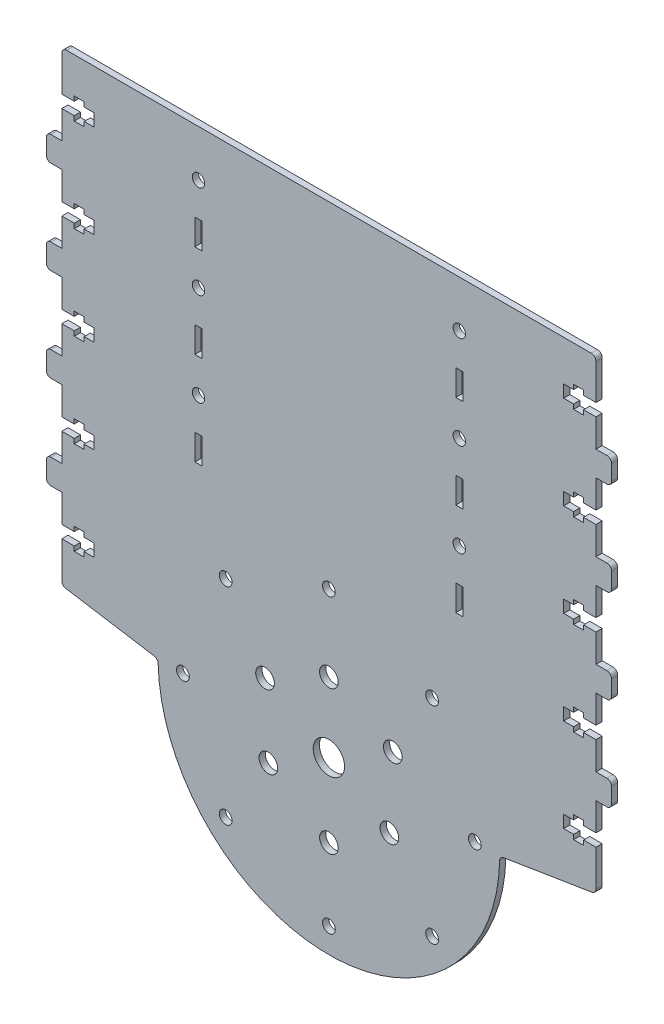
SolidWorks part; units mm, degrees
ref_plane "前视基准面" through (0, 0, 0) normal (0, 0, 1) x (1, 0, 0)
ref_plane "上视基准面" through (0, 0, 0) normal (0, 1, 0) x (1, 0, 0)
ref_plane "右视基准面" through (0, 0, 0) normal (1, 0, 0) x (0, 0, -1)
sketch "草图1" plane through (0, 0, 0) normal (0, 0, 1) x (1, 0, 0)
  line L9 (143, 46) -> (147, 46)
  line L10 (147, 46) -> (147, 44.5)
  line L11 (147, 44.5) -> (150.2, 44.5)
  line L12 (150.2, 44.5) -> (150.2, 46)
  line L13 (150.2, 46) -> (153.4, 46)
  line L14 (153.4, 46) -> (153.4, 50)
  line L23 (143, 48) -> (141.6922, 48) construction
  line L24 (143, 46) -> (143, 50) construction
  line L25 (150.2, 51.5) -> (150.2, 50)
  line L26 (147, 50) -> (147, 51.5)
  line L27 (150.2, 50) -> (153.4, 50)
  line L28 (147, 51.5) -> (150.2, 51.5)
  line L29 (143, 50) -> (147, 50)
  line L31 (143, 29) -> (138, 29)
  line L32 (138, 29) -> (138, 37)
  line L33 (138, 37) -> (143, 37)
  line L34 (143, 37) -> (143, 46)
  line L35 (138, 33) -> (143, 33) construction
  line L43 (143, 119) -> (143, 123)
  line L44 (229, -79) -> (229, -87) construction
  line L45 (143, 20) -> (143, 16) construction
  line L69 (143, -97) -> (311, -97) construction
  line L70 (143, 18) -> (141.6922, 18) construction
  line L71 (143, 16) -> (147, 16)
  line L72 (147, 16) -> (147, 14.5)
  line L73 (147, 14.5) -> (150.2, 14.5)
  line L98 (150.2, 14.5) -> (150.2, 16)
  line L123 (150.2, 16) -> (153.4, 16)
  line L124 (150.2, 21.5) -> (150.2, 20)
  line L125 (147, 20) -> (147, 21.5)
  line L126 (150.2, 20) -> (153.4, 20)
  line L127 (147, 21.5) -> (150.2, 21.5)
  line L128 (143, 20) -> (147, 20)
  line L129 (143, 7) -> (143, 16)
  line L130 (143, 16) -> (147, 16)
  line L131 (147, 14.5) -> (150.2, 14.5)
  line L132 (143, 16) -> (147, 16)
  line L133 (147, 16) -> (147, 14.5)
  line L134 (147, 14.5) -> (150.2, 14.5)
  line L135 (150.2, 14.5) -> (150.2, 16)
  line L136 (150.2, 16) -> (153.4, 16)
  line L137 (150.2, 21.5) -> (150.2, 20)
  line L138 (147, 20) -> (147, 21.5)
  line L139 (150.2, 20) -> (153.4, 20)
  line L140 (147, 21.5) -> (150.2, 21.5)
  line L141 (143, 20) -> (147, 20)
  line L142 (150.2, 16) -> (153.4, 16)
  line L143 (147, 16) -> (147, 14.5)
  line L144 (150.2, 14.5) -> (150.2, 16)
  line L145 (150.2, 20) -> (153.4, 20)
  line L146 (150.2, 21.5) -> (150.2, 20)
  line L147 (147, 21.5) -> (150.2, 21.5)
  line L148 (147, 20) -> (147, 21.5)
  line L149 (143, 20) -> (147, 20)
  line L150 (143, 46) -> (147, 46)
  line L151 (147, 46) -> (147, 44.5)
  line L152 (147, 44.5) -> (150.2, 44.5)
  line L153 (150.2, 44.5) -> (150.2, 46)
  line L154 (150.2, 46) -> (153.4, 46)
  line L155 (150.2, 51.5) -> (150.2, 50)
  line L156 (147, 50) -> (147, 51.5)
  line L157 (150.2, 50) -> (153.4, 50)
  line L158 (143, 46) -> (147, 46)
  line L159 (147, 44.5) -> (150.2, 44.5)
  line L160 (150.2, 46) -> (153.4, 46)
  line L161 (147, 46) -> (147, 44.5)
  line L162 (150.2, 44.5) -> (150.2, 46)
  line L163 (150.2, 50) -> (153.4, 50)
  line L164 (150.2, 51.5) -> (150.2, 50)
  line L165 (147, 51.5) -> (150.2, 51.5)
  line L166 (147, 50) -> (147, 51.5)
  line L167 (143, 50) -> (147, 50)
  line L168 (147, 51.5) -> (150.2, 51.5)
  line L169 (143, 50) -> (147, 50)
  line L170 (143, 29) -> (143, 20)
  line L171 (143, 16) -> (147, 16)
  line L172 (147, 14.5) -> (150.2, 14.5)
  line L173 (150.2, 16) -> (153.4, 16)
  line L174 (147, 16) -> (147, 14.5)
  line L175 (150.2, 14.5) -> (150.2, 16)
  line L177 (153.4, 20) -> (153.4, 16)
  line L178 (150.2, 20) -> (153.4, 20)
  line L179 (150.2, 21.5) -> (150.2, 20)
  line L180 (147, 21.5) -> (150.2, 21.5)
  line L181 (147, 20) -> (147, 21.5)
  line L182 (143, 20) -> (147, 20)
  line L183 (138, 3) -> (143, 3) construction
  line L184 (138, -1) -> (143, -1)
  line L185 (138, 7) -> (138, -1)
  line L186 (143, 7) -> (138, 7)
  line L187 (138, 93) -> (143, 93) construction
  line L188 (143, 78) -> (141.6922, 78) construction
  line L189 (272.15, 28.85) -> (269.85, 37.15) construction
  line L190 (138, 63) -> (143, 63) construction
  line L191 (143, 89) -> (138, 89)
  line L192 (138, 89) -> (138, 97)
  line L193 (138, 97) -> (143, 97)
  line L194 (143, 76) -> (147, 76)
  line L195 (147, 76) -> (147, 74.5)
  line L196 (147, 74.5) -> (150.2, 74.5)
  line L197 (150.2, 74.5) -> (150.2, 76)
  line L198 (150.2, 76) -> (153.4, 76)
  line L199 (143, 59) -> (143, 50)
  line L200 (138, 59) -> (143, 59)
  line L201 (153.4, 76) -> (153.4, 80)
  line L202 (150.2, 81.5) -> (150.2, 80)
  line L203 (143, 46) -> (147, 46)
  line L204 (147, 44.5) -> (150.2, 44.5)
  line L205 (150.2, 46) -> (153.4, 46)
  line L206 (147, 46) -> (147, 44.5)
  line L207 (150.2, 44.5) -> (150.2, 46)
  line L208 (150.2, 50) -> (153.4, 50)
  line L209 (150.2, 51.5) -> (150.2, 50)
  line L210 (147, 51.5) -> (150.2, 51.5)
  line L211 (147, 50) -> (147, 51.5)
  line L212 (143, 50) -> (147, 50)
  line L213 (272.15, 37.15) -> (269.85, 28.85) construction
  line L214 (147, 80) -> (147, 81.5)
  line L215 (150.2, 80) -> (153.4, 80)
  line L216 (147, 81.5) -> (150.2, 81.5)
  line L217 (143, 80) -> (147, 80)
  line L218 (143, 67) -> (143, 76)
  line L219 (143, 76) -> (147, 76)
  line L220 (147, 76) -> (147, 74.5)
  line L221 (147, 74.5) -> (150.2, 74.5)
  line L222 (150.2, 74.5) -> (150.2, 76)
  line L223 (150.2, 76) -> (153.4, 76)
  line L224 (150.2, 81.5) -> (150.2, 80)
  line L225 (147, 80) -> (147, 81.5)
  line L227 (271, 48) -> (271, 33) construction
  line L228 (272.15, 58.85) -> (269.85, 67.15) construction
  line L229 (272.15, 67.15) -> (269.85, 58.85) construction
  line L230 (150.2, 80) -> (153.4, 80)
  line L231 (143, 76) -> (147, 76)
  line L232 (147, 74.5) -> (150.2, 74.5)
  line L233 (150.2, 76) -> (153.4, 76)
  line L234 (147, 76) -> (147, 74.5)
  line L235 (150.2, 74.5) -> (150.2, 76)
  line L253 (150.2, 80) -> (153.4, 80)
  line L254 (150.2, 81.5) -> (150.2, 80)
  line L255 (143, -27) -> (143, -97) construction
  line L256 (147, 81.5) -> (150.2, 81.5)
  line L257 (147, 80) -> (147, 81.5)
  line L258 (143, 80) -> (147, 80)
  line L259 (147, 81.5) -> (150.2, 81.5)
  line L260 (143, 80) -> (147, 80)
  line L261 (143, 89) -> (143, 80)
  line L262 (143, 76) -> (147, 76)
  line L263 (147, 74.5) -> (150.2, 74.5)
  line L264 (150.2, 76) -> (153.4, 76)
  line L265 (147, 76) -> (147, 74.5)
  line L267 (150.2, 74.5) -> (150.2, 76)
  line L269 (150.2, 80) -> (153.4, 80)
  line L270 (150.2, 81.5) -> (150.2, 80)
  line L272 (147, 81.5) -> (150.2, 81.5)
  line L273 (147, 80) -> (147, 81.5)
  line L274 (143, 80) -> (147, 80)
  line L275 (138, 59) -> (143, 59)
  line L277 (138, 67) -> (138, 59)
  line L278 (143, 67) -> (138, 67)
  line L279 (143, 110) -> (143, 106) construction
  line L280 (143, 108) -> (141.6922, 108) construction
  line L281 (272.15, 88.85) -> (269.85, 97.15) construction
  line L282 (143, 106) -> (147, 106)
  line L283 (147, 106) -> (147, 104.5)
  line L284 (147, 104.5) -> (150.2, 104.5)
  line L285 (150.2, 104.5) -> (150.2, 106)
  line L286 (150.2, 106) -> (153.4, 106)
  line L287 (150.2, 111.5) -> (150.2, 110)
  line L288 (147, 110) -> (147, 111.5)
  line L289 (150.2, 110) -> (153.4, 110)
  line L290 (147, 111.5) -> (150.2, 111.5)
  line L291 (143, 110) -> (147, 110)
  line L292 (143, 97) -> (143, 106)
  line L293 (143, 106) -> (147, 106)
  line L294 (147, 104.5) -> (150.2, 104.5)
  line L296 (143, 106) -> (147, 106)
  line L300 (147, 106) -> (147, 104.5)
  line L301 (147, 104.5) -> (150.2, 104.5)
  line L302 (150.2, 104.5) -> (150.2, 106)
  line L303 (150.2, 106) -> (153.4, 106)
  line L304 (150.2, 111.5) -> (150.2, 110)
  line L305 (147, 110) -> (147, 111.5)
  line L306 (150.2, 110) -> (153.4, 110)
  line L307 (147, 111.5) -> (150.2, 111.5)
  line L308 (143, 110) -> (147, 110)
  line L309 (150.2, 106) -> (153.4, 106)
  line L310 (147, 106) -> (147, 104.5)
  line L312 (150.2, 104.5) -> (150.2, 106)
  line L314 (150.2, 110) -> (153.4, 110)
  line L315 (150.2, 111.5) -> (150.2, 110)
  line L317 (147, 111.5) -> (150.2, 111.5)
  line L320 (147, 110) -> (147, 111.5)
  line L321 (143, 110) -> (147, 110)
  line L322 (143, 119) -> (143, 110)
  line L323 (143, 106) -> (147, 106)
  line L324 (147, 104.5) -> (150.2, 104.5)
  line L325 (150.2, 106) -> (153.4, 106)
  line L326 (147, 106) -> (147, 104.5)
  line L327 (150.2, 104.5) -> (150.2, 106)
  line L328 (153.4, 110) -> (153.4, 106)
  line L329 (150.2, 110) -> (153.4, 110)
  line L330 (150.2, 111.5) -> (150.2, 110)
  line L331 (147, 111.5) -> (150.2, 111.5)
  line L332 (147, 110) -> (147, 111.5)
  line L333 (143, 110) -> (147, 110)
  line L334 (143, -14) -> (147, -14)
  line L335 (272.15, 97.15) -> (269.85, 88.85) construction
  line L336 (271, 108) -> (271, 48) construction
  line L337 (269.85, 37.15) -> (269.85, 28.85)
  line L338 (272.15, 28.85) -> (269.85, 28.85)
  line L339 (272.15, 37.15) -> (272.15, 28.85)
  line L340 (272.15, 37.15) -> (269.85, 37.15)
  line L341 (269.85, 67.15) -> (269.85, 58.85)
  line L342 (272.15, 58.85) -> (269.85, 58.85)
  line L343 (272.15, 67.15) -> (272.15, 58.85)
  line L344 (272.15, 67.15) -> (269.85, 67.15)
  line L345 (269.85, 97.15) -> (269.85, 88.85)
  line L346 (272.15, 88.85) -> (269.85, 88.85)
  line L347 (272.15, 97.15) -> (272.15, 88.85)
  line L348 (272.15, 97.15) -> (269.85, 97.15)
  line L349 (307.8, 110) -> (304.6, 110)
  line L350 (304.6, 110) -> (304.6, 106)
  line L352 (307.8, 106) -> (304.6, 106)
  line L353 (307.8, 110) -> (304.6, 110)
  line L355 (307.8, 106) -> (304.6, 106)
  line L357 (307.8, 110) -> (304.6, 110)
  line L358 (307.8, 106) -> (304.6, 106)
  line L359 (307.8, 110) -> (304.6, 110)
  line L360 (307.8, 106) -> (304.6, 106)
  line L361 (307.8, 80) -> (304.6, 80)
  line L362 (307.8, 76) -> (304.6, 76)
  line L363 (307.8, 80) -> (304.6, 80)
  line L364 (307.8, 76) -> (304.6, 76)
  line L365 (307.8, 80) -> (304.6, 80)
  line L367 (307.8, 76) -> (304.6, 76)
  line L369 (187, 108) -> (187, 48) construction
  line L370 (185.85, 97.15) -> (188.15, 97.15)
  line L371 (185.85, 97.15) -> (185.85, 88.85)
  line L372 (185.85, 88.85) -> (188.15, 88.85)
  line L373 (188.15, 97.15) -> (188.15, 88.85)
  line L374 (185.85, 97.15) -> (188.15, 88.85) construction
  line L375 (185.85, 88.85) -> (188.15, 97.15) construction
  line L387 (307.8, 80) -> (304.6, 80)
  line L389 (307.8, 50) -> (304.6, 50)
  line L391 (307.8, 46) -> (304.6, 46)
  line L392 (304.6, 76) -> (304.6, 80)
  line L420 (307.8, 76) -> (304.6, 76)
  line L421 (229, -32) -> (245.7973, -32) construction
  line L422 (229, -32) -> (253.7224, -46.2735) construction
  line L423 (185.85, 67.15) -> (188.15, 67.15)
  line L424 (185.85, 67.15) -> (185.85, 58.85)
  line L425 (185.85, 58.85) -> (188.15, 58.85)
  line L426 (188.15, 67.15) -> (188.15, 58.85)
  line L427 (185.85, 67.15) -> (188.15, 58.85) construction
  line L432 (185.85, 58.85) -> (188.15, 67.15) construction
  line L433 (307.8, 20) -> (304.6, 20)
  line L443 (187, 48) -> (187, 33) construction
  line L444 (304.6, 20) -> (304.6, 16)
  line L445 (185.85, 37.15) -> (188.15, 37.15)
  line L446 (185.85, 37.15) -> (185.85, 28.85)
  line L447 (185.85, 28.85) -> (188.15, 28.85)
  line L448 (188.15, 37.15) -> (188.15, 28.85)
  line L449 (185.85, 37.15) -> (188.15, 28.85) construction
  line L450 (185.85, 28.85) -> (188.15, 37.15) construction
  line L451 (307.8, 16) -> (304.6, 16)
  line L452 (307.8, 50) -> (304.6, 50)
  line L453 (307.8, 46) -> (304.6, 46)
  line L454 (307.8, 50) -> (304.6, 50)
  line L455 (307.8, 46) -> (304.6, 46)
  line L456 (307.8, 20) -> (304.6, 20)
  line L457 (307.8, 16) -> (304.6, 16)
  line L458 (307.8, 20) -> (304.6, 20)
  line L459 (307.8, 16) -> (304.6, 16)
  line L460 (307.8, 20) -> (304.6, 20)
  line L461 (307.8, 16) -> (304.6, 16)
  line L462 (307.8, 50) -> (304.6, 50)
  line L463 (304.6, 46) -> (304.6, 50)
  line L464 (307.8, 46) -> (304.6, 46)
  line L465 (315, 108) -> (316.3078, 108) construction
  line L466 (315, 110) -> (315, 106) construction
  line L467 (320, 63) -> (315, 63) construction
  line L468 (315, 78) -> (316.3078, 78) construction
  line L469 (320, 93) -> (315, 93) construction
  line L470 (320, 3) -> (315, 3) construction
  line L471 (315, 18) -> (316.3078, 18) construction
  line L472 (315, 20) -> (315, 16) construction
  line L473 (320, 33) -> (315, 33) construction
  line L474 (315, 46) -> (315, 50) construction
  line L475 (315, 48) -> (316.3078, 48) construction
  line L476 (315, -14) -> (315, -27)
  line L477 (315, 110) -> (311, 110)
  line L478 (311, 110) -> (311, 111.5)
  line L479 (311, 111.5) -> (307.8, 111.5)
  line L480 (307.8, 111.5) -> (307.8, 110)
  line L481 (307.8, 104.5) -> (307.8, 106)
  line L482 (311, 106) -> (311, 104.5)
  line L483 (311, 104.5) -> (307.8, 104.5)
  line L484 (315, 106) -> (311, 106)
  line L485 (315, 119) -> (315, 110)
  line L486 (315, 110) -> (311, 110)
  line L487 (311, 110) -> (311, 111.5)
  line L488 (311, 111.5) -> (307.8, 111.5)
  line L489 (307.8, 111.5) -> (307.8, 110)
  line L490 (307.8, 104.5) -> (307.8, 106)
  line L491 (311, 106) -> (311, 104.5)
  line L492 (315, 110) -> (311, 110)
  line L493 (311, 111.5) -> (307.8, 111.5)
  line L494 (311, 110) -> (311, 111.5)
  line L495 (307.8, 111.5) -> (307.8, 110)
  line L496 (307.8, 104.5) -> (307.8, 106)
  line L497 (311, 104.5) -> (307.8, 104.5)
  line L498 (311, 106) -> (311, 104.5)
  line L499 (315, 106) -> (311, 106)
  line L500 (311, 104.5) -> (307.8, 104.5)
  line L501 (315, 106) -> (311, 106)
  line L502 (315, 97) -> (315, 106)
  line L503 (315, 110) -> (311, 110)
  line L504 (311, 111.5) -> (307.8, 111.5)
  line L505 (311, 110) -> (311, 111.5)
  line L506 (307.8, 111.5) -> (307.8, 110)
  line L507 (307.8, 104.5) -> (307.8, 106)
  line L508 (311, 104.5) -> (307.8, 104.5)
  line L509 (311, 106) -> (311, 104.5)
  line L510 (315, 106) -> (311, 106)
  line L511 (315, 67) -> (320, 67)
  line L512 (320, 67) -> (320, 59)
  line L513 (320, 59) -> (315, 59)
  line L514 (315, 80) -> (311, 80)
  line L515 (311, 80) -> (311, 81.5)
  line L516 (311, 81.5) -> (307.8, 81.5)
  line L517 (307.8, 81.5) -> (307.8, 80)
  line L518 (307.8, 74.5) -> (307.8, 76)
  line L519 (311, 76) -> (311, 74.5)
  line L520 (311, 74.5) -> (307.8, 74.5)
  line L521 (315, 76) -> (311, 76)
  line L522 (315, 89) -> (315, 80)
  line L523 (315, 80) -> (311, 80)
  line L524 (311, 81.5) -> (307.8, 81.5)
  line L525 (315, 80) -> (311, 80)
  line L526 (311, 80) -> (311, 81.5)
  line L527 (311, 81.5) -> (307.8, 81.5)
  line L528 (307.8, 81.5) -> (307.8, 80)
  line L529 (307.8, 74.5) -> (307.8, 76)
  line L530 (311, 76) -> (311, 74.5)
  line L531 (311, 74.5) -> (307.8, 74.5)
  line L532 (315, 76) -> (311, 76)
  line L533 (311, 80) -> (311, 81.5)
  line L534 (307.8, 81.5) -> (307.8, 80)
  line L535 (307.8, 74.5) -> (307.8, 76)
  line L536 (311, 74.5) -> (307.8, 74.5)
  line L537 (311, 76) -> (311, 74.5)
  line L538 (315, 76) -> (311, 76)
  line L539 (315, 67) -> (315, 76)
  line L540 (315, 80) -> (311, 80)
  line L541 (311, 81.5) -> (307.8, 81.5)
  line L542 (311, 80) -> (311, 81.5)
  line L543 (315, 50) -> (311, 50)
  line L544 (311, 50) -> (311, 51.5)
  line L545 (311, 51.5) -> (307.8, 51.5)
  line L546 (307.8, 51.5) -> (307.8, 50)
  line L547 (307.8, 44.5) -> (307.8, 46)
  line L548 (311, 46) -> (311, 44.5)
  line L549 (311, 44.5) -> (307.8, 44.5)
  line L550 (315, 46) -> (311, 46)
  line L551 (307.8, 81.5) -> (307.8, 80)
  line L552 (320, 59) -> (315, 59)
  line L553 (315, 59) -> (315, 50)
  line L554 (307.8, 74.5) -> (307.8, 76)
  line L555 (311, 74.5) -> (307.8, 74.5)
  line L556 (311, 76) -> (311, 74.5)
  line L557 (315, 76) -> (311, 76)
  line L558 (320, 97) -> (315, 97)
  line L559 (320, 89) -> (320, 97)
  line L560 (315, 89) -> (320, 89)
  line L561 (315, 7) -> (320, 7)
  line L562 (320, 7) -> (320, -1)
  line L563 (320, -1) -> (315, -1)
  line L564 (315, 20) -> (311, 20)
  line L565 (311, 20) -> (311, 21.5)
  line L566 (311, 21.5) -> (307.8, 21.5)
  line L567 (307.8, 21.5) -> (307.8, 20)
  line L568 (307.8, 14.5) -> (307.8, 16)
  line L569 (311, 16) -> (311, 14.5)
  line L570 (311, 14.5) -> (307.8, 14.5)
  line L571 (315, 16) -> (311, 16)
  line L572 (315, 29) -> (315, 20)
  line L573 (315, 50) -> (311, 50)
  line L574 (311, 51.5) -> (307.8, 51.5)
  line L575 (315, 50) -> (311, 50)
  line L576 (311, 50) -> (311, 51.5)
  line L577 (311, 51.5) -> (307.8, 51.5)
  line L578 (307.8, 51.5) -> (307.8, 50)
  line L579 (307.8, 44.5) -> (307.8, 46)
  line L580 (311, 46) -> (311, 44.5)
  line L581 (311, 44.5) -> (307.8, 44.5)
  line L582 (315, 46) -> (311, 46)
  line L583 (311, 50) -> (311, 51.5)
  line L584 (307.8, 51.5) -> (307.8, 50)
  line L585 (307.8, 44.5) -> (307.8, 46)
  line L586 (311, 44.5) -> (307.8, 44.5)
  line L587 (311, 46) -> (311, 44.5)
  line L588 (315, 46) -> (311, 46)
  line L589 (315, 20) -> (311, 20)
  line L590 (311, 20) -> (311, 21.5)
  line L591 (311, 21.5) -> (307.8, 21.5)
  line L592 (307.8, 21.5) -> (307.8, 20)
  line L593 (307.8, 14.5) -> (307.8, 16)
  line L594 (311, 16) -> (311, 14.5)
  line L595 (315, 20) -> (311, 20)
  line L596 (311, 21.5) -> (307.8, 21.5)
  line L597 (311, 20) -> (311, 21.5)
  line L598 (307.8, 21.5) -> (307.8, 20)
  line L599 (307.8, 14.5) -> (307.8, 16)
  line L600 (311, 14.5) -> (307.8, 14.5)
  line L601 (311, 16) -> (311, 14.5)
  line L602 (315, 16) -> (311, 16)
  line L603 (311, 14.5) -> (307.8, 14.5)
  line L604 (315, 16) -> (311, 16)
  line L605 (315, 7) -> (315, 16)
  line L606 (315, 20) -> (311, 20)
  line L607 (311, 21.5) -> (307.8, 21.5)
  line L608 (311, 20) -> (311, 21.5)
  line L609 (307.8, 21.5) -> (307.8, 20)
  line L610 (307.8, 14.5) -> (307.8, 16)
  line L611 (311, 14.5) -> (307.8, 14.5)
  line L612 (311, 16) -> (311, 14.5)
  line L613 (315, 16) -> (311, 16)
  line L614 (315, 119) -> (315, 123)
  line L615 (315, 37) -> (315, 46)
  line L616 (320, 37) -> (315, 37)
  line L617 (320, 29) -> (320, 37)
  line L618 (315, 29) -> (320, 29)
  line L619 (315, 50) -> (311, 50)
  line L620 (311, 51.5) -> (307.8, 51.5)
  line L621 (311, 50) -> (311, 51.5)
  line L622 (307.8, 51.5) -> (307.8, 50)
  line L623 (307.8, 44.5) -> (307.8, 46)
  line L624 (311, 44.5) -> (307.8, 44.5)
  line L625 (311, 46) -> (311, 44.5)
  line L626 (315, 46) -> (311, 46)
  line L627 (315, 123) -> (143, 123)
  line L628 (143, -27) -> (174, -32)
  line L629 (284, -32) -> (315, -27)
  line L630 (147, -14) -> (147, -15.5)
  line L631 (147, -15.5) -> (150.2, -15.5)
  line L632 (150.2, -15.5) -> (150.2, -14)
  line L633 (150.2, -14) -> (153.4, -14)
  line L634 (153.4, -14) -> (153.4, -10)
  line L635 (150.2, -8.5) -> (150.2, -10)
  line L636 (147, -10) -> (147, -8.5)
  line L637 (150.2, -10) -> (153.4, -10)
  line L638 (147, -8.5) -> (150.2, -8.5)
  line L639 (143, -10) -> (147, -10)
  line L640 (143, -14) -> (147, -14)
  line L641 (147, -14) -> (147, -15.5)
  line L642 (147, -15.5) -> (150.2, -15.5)
  line L643 (150.2, -15.5) -> (150.2, -14)
  line L644 (150.2, -14) -> (153.4, -14)
  line L645 (150.2, -8.5) -> (150.2, -10)
  line L646 (147, -10) -> (147, -8.5)
  line L647 (150.2, -10) -> (153.4, -10)
  line L648 (143, -14) -> (147, -14)
  line L649 (147, -15.5) -> (150.2, -15.5)
  line L650 (150.2, -14) -> (153.4, -14)
  line L651 (147, -14) -> (147, -15.5)
  line L652 (150.2, -15.5) -> (150.2, -14)
  line L653 (150.2, -10) -> (153.4, -10)
  line L654 (150.2, -8.5) -> (150.2, -10)
  line L655 (147, -8.5) -> (150.2, -8.5)
  line L656 (147, -10) -> (147, -8.5)
  line L657 (143, -10) -> (147, -10)
  line L658 (147, -8.5) -> (150.2, -8.5)
  line L659 (143, -10) -> (147, -10)
  line L660 (143, -14) -> (147, -14)
  line L661 (147, -15.5) -> (150.2, -15.5)
  line L662 (150.2, -14) -> (153.4, -14)
  line L663 (147, -14) -> (147, -15.5)
  line L664 (150.2, -15.5) -> (150.2, -14)
  line L665 (150.2, -10) -> (153.4, -10)
  line L666 (150.2, -8.5) -> (150.2, -10)
  line L667 (147, -8.5) -> (150.2, -8.5)
  line L668 (147, -10) -> (147, -8.5)
  line L669 (143, -10) -> (147, -10)
  line L670 (143, -10) -> (143, -1)
  line L671 (143, -14) -> (143, -27)
  line L672 (315, -10) -> (315, -1)
  line L673 (315, -10) -> (311, -10)
  line L674 (311, -10) -> (311, -8.5)
  line L675 (311, -8.5) -> (307.8, -8.5)
  line L676 (307.8, -8.5) -> (307.8, -10)
  line L677 (307.8, -10) -> (304.6, -10)
  line L678 (307.8, -15.5) -> (307.8, -14)
  line L679 (311, -14) -> (311, -15.5)
  line L680 (307.8, -14) -> (304.6, -14)
  line L681 (311, -15.5) -> (307.8, -15.5)
  line L682 (315, -14) -> (311, -14)
  line L683 (315, -10) -> (311, -10)
  line L684 (311, -8.5) -> (307.8, -8.5)
  line L685 (315, -10) -> (311, -10)
  line L686 (311, -10) -> (311, -8.5)
  line L687 (311, -8.5) -> (307.8, -8.5)
  line L688 (307.8, -8.5) -> (307.8, -10)
  line L689 (307.8, -10) -> (304.6, -10)
  line L690 (307.8, -15.5) -> (307.8, -14)
  line L691 (311, -14) -> (311, -15.5)
  line L692 (307.8, -14) -> (304.6, -14)
  line L693 (311, -15.5) -> (307.8, -15.5)
  line L694 (315, -14) -> (311, -14)
  line L695 (307.8, -10) -> (304.6, -10)
  line L696 (311, -10) -> (311, -8.5)
  line L697 (307.8, -8.5) -> (307.8, -10)
  line L698 (307.8, -14) -> (304.6, -14)
  line L699 (307.8, -15.5) -> (307.8, -14)
  line L700 (311, -15.5) -> (307.8, -15.5)
  line L701 (311, -14) -> (311, -15.5)
  line L702 (315, -14) -> (311, -14)
  line L703 (315, -10) -> (311, -10)
  line L704 (311, -8.5) -> (307.8, -8.5)
  line L705 (307.8, -10) -> (304.6, -10)
  line L706 (311, -10) -> (311, -8.5)
  line L707 (307.8, -8.5) -> (307.8, -10)
  line L708 (304.6, -14) -> (304.6, -10)
  line L709 (307.8, -14) -> (304.6, -14)
  line L710 (307.8, -15.5) -> (307.8, -14)
  line L711 (311, -15.5) -> (307.8, -15.5)
  line L712 (311, -14) -> (311, -15.5)
  line L713 (315, -14) -> (311, -14)
  circle A88 centre (187, 108) radius 2
  circle A97 centre (229, -32) radius 23.75 construction
  circle A98 centre (229, -32) radius 22.5 construction
  circle A99 centre (229, -55.75) radius 3
  circle A100 centre (248.4856, -43.25) radius 3
  circle A101 centre (229, -32) radius 5.05
  circle A102 centre (276, -32) radius 2.05
  circle A103 centre (208.4319, -20.125) radius 3
  circle A104 centre (249.5681, -20.125) radius 3
  circle A105 centre (209.5144, -43.25) radius 3
  circle A106 centre (229, -9.5) radius 3
  circle A114 centre (187, 78) radius 2
  circle A115 centre (187, 48) radius 2
  circle A119 centre (262.234, -65.234) radius 2.05
  circle A120 centre (229, -79) radius 2.05
  circle A121 centre (195.766, -65.234) radius 2.05
  circle A122 centre (182, -32) radius 2.05
  circle A123 centre (195.766, 1.234) radius 2.05
  circle A124 centre (229, 15) radius 2.05
  circle A125 centre (262.234, 1.234) radius 2.05
  circle A126 centre (229, -32) radius 55 construction
  arc A127 (174, -32) -> (284, -32) centre (229, -32) ccw
  circle A128 centre (271, 48) radius 2
  circle A129 centre (271, 78) radius 2
  circle A130 centre (271, 108) radius 2
  point P15 (142.3461, 48)
  point P103 (271, 63)
  point P104 (271, 93)
  point P199 (187, 93)
  point P208 (187, 63)
  dimension "D7" = 8
  dimension "D9" = 10.1
  dimension "D11" = 2.3
  dimension "D13" = 15
  dimension "D15" = 47.5
  dimension "D16" = 45
  dimension "D17" = 6
  dimension "D19" = 6
  dimension "D21" = 4.1
  dimension "D22" = 4
  dimension "D25" = 30
  dimension "D3" = 4
  dimension "D4" = 172
  dimension "D5" = 3.2
  dimension "D6" = 7
  dimension "D8" = 2
  dimension "D12" = 8.3
  dimension "D18" = 30
  dimension "D20" = 47
  dimension "D23" = 15
  dimension "D24" = 8
extrude "凸台-拉伸1" add sketch "草图1" along normal blind 2
sketch "草图2" plane through (143, 0, 0) normal (-1, 0, 0) x (0, 0, 1)
  line L0 (1, 20) -> (1, 16)
  line L1 (2, 20) -> (0, 20) construction
  line L2 (2, 16) -> (0, 16) construction
  circle A0 centre (1, 18) radius 2
sketch "草图3" plane through (315, 0, 0) normal (1, 0, 0) x (0, 0, -1)
  line L0 (-1, 16) -> (-1, 20)
  line L1 (-2, 16) -> (0, 16) construction
  line L2 (-2, 20) -> (0, 20) construction
  circle A0 centre (-1, 18) radius 2
fillet "圆角1" radius 1.5 22 edges at (284, -32, 1) (174, -32, 1) (315, 123, 1) (143, 123, 1) (138, 97, 1) (138, 67, 1) (138, 37, 1) (138, 29, 1) (138, 59, 1) (138, 89, 1) (138, 7, 1) (138, -1, 1) (143, -27, 1) (315, -27, 1) (320, 89, 1) (320, 97, 1) (320, 67, 1) (320, 59, 1) (320, 37, 1) (320, 29, 1) (320, 7, 1) (320, -1, 1)
